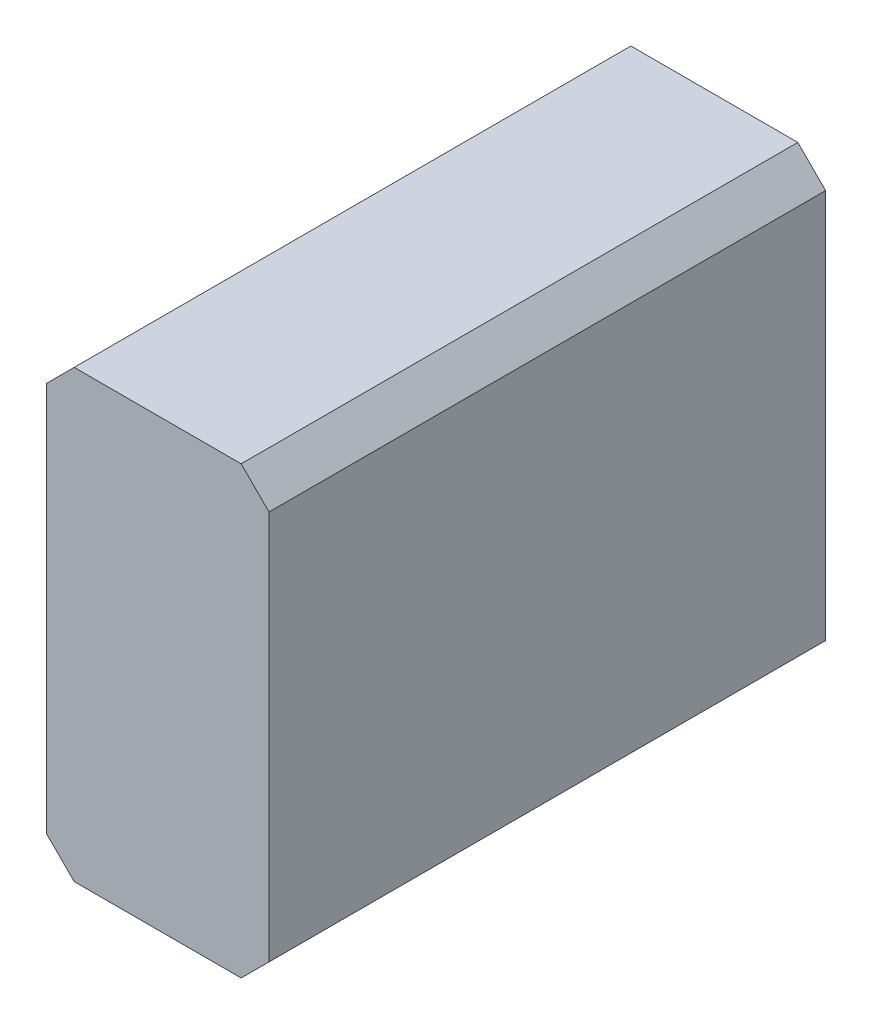
SolidWorks part; units mm, degrees
ref_plane "Front Plane" through (0, 0, 0) normal (0, 0, 1) x (1, 0, 0)
ref_plane "Top Plane" through (0, 0, 0) normal (0, 1, 0) x (1, 0, 0)
ref_plane "Right Plane" through (0, 0, 0) normal (1, 0, 0) x (0, 0, -1)
sketch "Sketch1" plane through (0, 0, 0) normal (0, 0, 1) x (1, 0, 0)
  line L1 (-2, 4) -> (2, 4)
  line L2 (-2, 4) -> (-2, -4)
  line L3 (-2, -4) -> (2, -4)
  line L4 (2, 4) -> (2, -4)
  line L5 (-2, 4) -> (2, -4) construction
  line L6 (-2, -4) -> (2, 4) construction
  point P0 (0, 0)
  dimension "D1" = 4
  dimension "D2" = 8
extrude "Boss-Extrude1" add sketch "Sketch1" along normal blind 10
chamfer "Chamfer1" distance 0.5 angle 45 4 edges at (-2, -4, 5) (2, -4, 5) (2, 4, 5) (-2, 4, 5)
